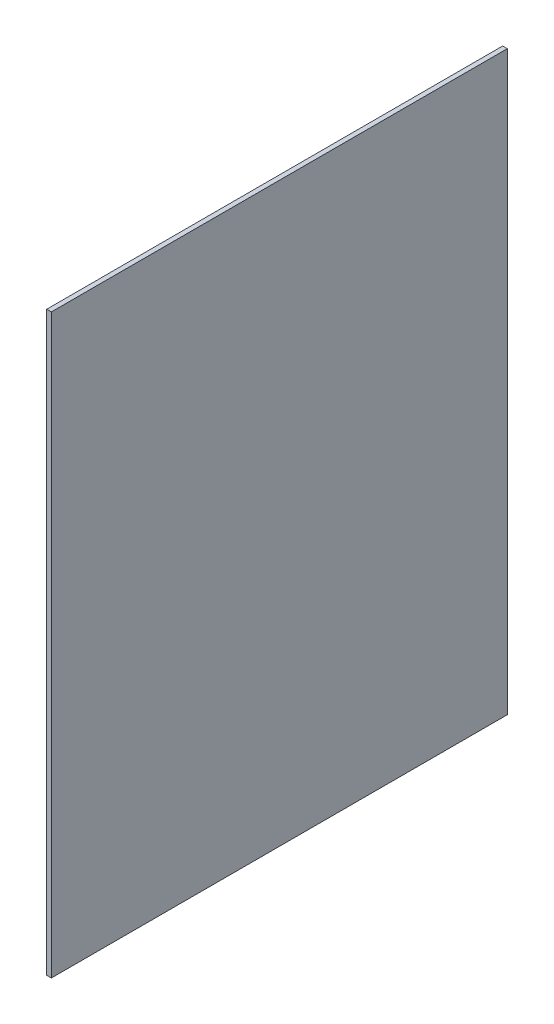
SolidWorks part; units mm, degrees
material "Beech"
ref_plane "Front Plane" through (0, 0, 0) normal (0, 0, 1) x (1, 0, 0)
ref_plane "Top Plane" through (0, 0, 0) normal (0, 1, 0) x (1, 0, 0)
ref_plane "Right Plane" through (0, 0, 0) normal (1, 0, 0) x (0, 0, -1)
sketch "Sketch1" plane through (0, 0, 0) normal (1, 0, 0) x (0, 0, -1)
  line L1 (0, 0) -> (-622.3, 0)
  line L2 (0, 0) -> (0, 787.4)
  line L3 (0, 787.4) -> (-622.3, 787.4)
  line L4 (-622.3, 0) -> (-622.3, 787.4)
  dimension "D1" = 622.3
  dimension "D2" = 787.4
extrude "Boss-Extrude1" add sketch "Sketch1" along normal blind 6.35
